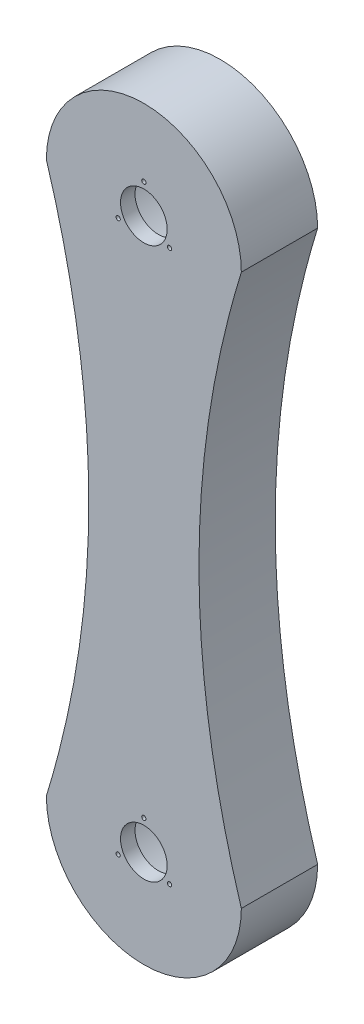
SolidWorks part; units mm, degrees
ref_plane "Front Plane" through (0, 0, 0) normal (1, 0, 0) x (0, 1, 0)
ref_plane "Top Plane" through (0, 0, 0) normal (0, 0, 1) x (0, 1, 0)
ref_plane "Right Plane" through (0, 0, 0) normal (0, 1, 0) x (-1, 0, 0)
sketch "Sketch1" plane through (0, 0, 0) normal (0, 0, 1) x (0, 1, 0)
  line L0 (0, 0) -> (650, 0) construction
  arc A0 (0, 115) -> (0, -115) centre (0, 0) ccw
  arc A1 (650, -115) -> (650, 115) centre (650, 0) ccw
  spline S0 degree 2 poles (0, 115) (325, 15) (650, 115) knots 0 0 0 1 1 1
  spline S1 degree 2 poles (0, -115) (325, -15) (650, -115) knots 0 0 0 1 1 1
  point P12 (325, 0)
  dimension "D1" = 230
  dimension "D2" = 650
  dimension "D3" = 130
extrude "Boss-Extrude1" add sketch "Sketch1" along normal blind 90
sketch "Sketch2" plane through (0, 0, 0) normal (0, 0, -1) x (1, 0, 0)
  circle A0 centre (0, 0) radius 97.5
  dimension "D1" = 195
extrude "Cut-Extrude1" cut sketch "Sketch2" against normal blind 72.91
sketch "Sketch3" plane through (0, 0, 72.91) normal (0, 0, -1) x (1, 0, 0)
  circle A0 centre (0, 0) radius 27.5
  dimension "D1" = 55
sketch "Sketch4" plane through (0, 0, 90) normal (0, 0, 1) x (1, 0, 0)
  line L0 (0, 0) -> (0, 35) construction
  circle A0 centre (0, 35) radius 2.5
  dimension "D1" = 5
  dimension "D2" = 35
extrude "Cut-Extrude3" cut sketch "Sketch4" against normal blind 20
extrude "Cut-Extrude4" cut sketch "Sketch3" against normal blind 20
pattern_circular "CirPattern2" count 3 every 120 about axis through (0, 0, 0) along (0, 0, 1) of "Cut-Extrude3"
sketch "Sketch6" plane through (0, 0, 0) normal (0, 0, -1) x (1, 0, 0)
  circle A0 centre (0, -650) radius 97.5
  circle A1 centre (0, 0) radius 97.5 construction
extrude "Cut-Extrude5" cut sketch "Sketch6" against normal blind 72.91
sketch "Sketch7" plane through (0, 0, 72.91) normal (0, 0, -1) x (1, 0, 0)
  circle A0 centre (0, -650) radius 27.5
  dimension "D1" = 55
extrude "Cut-Extrude6" cut sketch "Sketch7" against normal blind 72.91
sketch "Sketch8" plane through (0, 0, 90) normal (0, 0, 1) x (1, 0, 0)
  line L0 (0, 650) -> (0, 685) construction
  line L1 (0, 650) -> (-30.3109, 632.5) construction
  line L2 (0, 650) -> (30.3109, 632.5) construction
  circle A0 centre (-30.3109, 632.5) radius 2.5
  circle A1 centre (0, 685) radius 2.5
  circle A2 centre (30.3109, 632.5) radius 2.5
  circle A3 centre (-30.3109, -17.5) radius 2.5 construction
  circle A4 centre (30.3109, -17.5) radius 2.5 construction
  circle A5 centre (0, 35) radius 2.5 construction
  circle A6 centre (30.3109, -17.5) radius 2.5
  circle A7 centre (0, 35) radius 2.5
  circle A8 centre (-30.3109, -17.5) radius 2.5
  circle A9 centre (0, 650) radius 27.5 construction
  circle A10 centre (0, 650) radius 27.5
  dimension "D1" = 120
  dimension "D2" = 120
  dimension "D3" = 35
extrude "Cut-Extrude7" cut sketch "Sketch8" against normal blind 72.91
